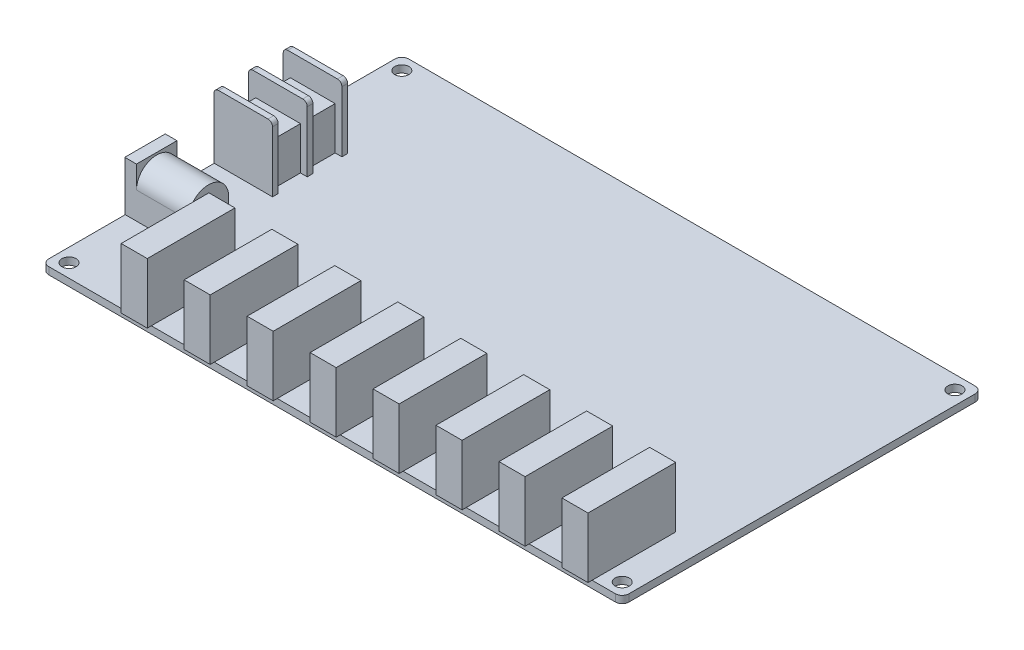
SolidWorks part; units mm, degrees
ref_plane "前视基准面" through (0, 0, 0) normal (0, 0, 1) x (1, 0, 0)
ref_plane "上视基准面" through (0, 0, 0) normal (0, 1, 0) x (1, 0, 0)
ref_plane "右视基准面" through (0, 0, 0) normal (1, 0, 0) x (0, 0, -1)
other "Configuration Table"
sketch "草图1" plane through (0, 0, 0) normal (0, 1, 0) x (1, 0, 0)
  line L0 (39.2697, 0) -> (168.2697, 0)
  line L1 (168.2697, 0) -> (168.2697, 80)
  line L2 (168.2697, 80) -> (39.2697, 80)
  line L3 (39.2697, 80) -> (39.2697, 0)
extrude "凸台-拉伸1" add sketch "草图1" along normal blind 1.6 contours L3 L0 L1 L2
sketch "草图2" plane through (0, 1.6, 0) normal (0, 1, 0) x (1, 0, 0)
  circle A0 centre (42.2697, 77) radius 1.575
  circle A1 centre (42.2697, 3) radius 1.575
  circle A2 centre (165.2697, 3) radius 1.575
  circle A3 centre (165.2697, 77) radius 1.575
extrude "切除-拉伸1" cut sketch "草图2" against normal through all
sketch "草图3" plane through (0, 1.6, 0) normal (0, 1, 0) x (1, 0, 0)
  line L0 (39.2697, 0) -> (57.7697, 0)
  line L1 (39.2697, 0) -> (168.2697, 0) construction
  line L2 (57.7697, 0) -> (57.7697, 18.6)
  line L3 (57.7697, 18.6) -> (63.5697, 18.6)
  line L4 (63.5697, 18.6) -> (63.5697, 0)
  line L34 (57.7697, 0) -> (57.7697, -0.9)
  line L35 (57.7697, -0.9) -> (63.5697, -0.9)
  line L36 (63.5697, -0.9) -> (63.5697, 0)
  line L40 (53.2697, 0) -> (71.7697, 0)
  line L41 (71.7697, 0) -> (71.7697, 18.6)
  line L42 (71.7697, 18.6) -> (77.5697, 18.6)
  line L43 (77.5697, 18.6) -> (77.5697, 0)
  line L44 (71.7697, 0) -> (71.7697, -0.9)
  line L45 (71.7697, -0.9) -> (77.5697, -0.9)
  line L46 (77.5697, -0.9) -> (77.5697, 0)
  line L47 (67.2697, 0) -> (85.7697, 0)
  line L48 (85.7697, 0) -> (85.7697, 18.6)
  line L49 (85.7697, 18.6) -> (91.5697, 18.6)
  line L50 (91.5697, 18.6) -> (91.5697, 0)
  line L51 (85.7697, 0) -> (85.7697, -0.9)
  line L52 (85.7697, -0.9) -> (91.5697, -0.9)
  line L53 (91.5697, -0.9) -> (91.5697, 0)
  line L54 (81.2697, 0) -> (99.7697, 0)
  line L55 (99.7697, 0) -> (99.7697, 18.6)
  line L56 (99.7697, 18.6) -> (105.5697, 18.6)
  line L57 (105.5697, 18.6) -> (105.5697, 0)
  line L58 (99.7697, 0) -> (99.7697, -0.9)
  line L59 (99.7697, -0.9) -> (105.5697, -0.9)
  line L60 (105.5697, -0.9) -> (105.5697, 0)
  line L61 (95.2697, 0) -> (113.7697, 0)
  line L62 (113.7697, 0) -> (113.7697, 18.6)
  line L63 (113.7697, 18.6) -> (119.5697, 18.6)
  line L64 (119.5697, 18.6) -> (119.5697, 0)
  line L65 (113.7697, 0) -> (113.7697, -0.9)
  line L66 (113.7697, -0.9) -> (119.5697, -0.9)
  line L67 (119.5697, -0.9) -> (119.5697, 0)
  line L68 (109.2697, 0) -> (127.7697, 0)
  line L69 (127.7697, 0) -> (127.7697, 18.6)
  line L70 (127.7697, 18.6) -> (133.5697, 18.6)
  line L71 (133.5697, 18.6) -> (133.5697, 0)
  line L72 (127.7697, 0) -> (127.7697, -0.9)
  line L73 (127.7697, -0.9) -> (133.5697, -0.9)
  line L74 (133.5697, -0.9) -> (133.5697, 0)
  line L75 (123.2697, 0) -> (141.7697, 0)
  line L76 (141.7697, 0) -> (141.7697, 18.6)
  line L77 (141.7697, 18.6) -> (147.5697, 18.6)
  line L78 (147.5697, 18.6) -> (147.5697, 0)
  line L79 (141.7697, 0) -> (141.7697, -0.9)
  line L80 (141.7697, -0.9) -> (147.5697, -0.9)
  line L81 (147.5697, -0.9) -> (147.5697, 0)
  line L82 (137.2697, 0) -> (155.7697, 0)
  line L83 (155.7697, 0) -> (155.7697, 18.6)
  line L84 (155.7697, 18.6) -> (161.5697, 18.6)
  line L85 (161.5697, 18.6) -> (161.5697, 0)
  line L86 (155.7697, 0) -> (155.7697, -0.9)
  line L87 (155.7697, -0.9) -> (161.5697, -0.9)
  line L88 (161.5697, -0.9) -> (161.5697, 0)
  line M11 (39.2697, 0) -> (168.2697, 0)
  dimension "D1" = 8
extrude "凸台-拉伸2" add sketch "草图3" along normal blind 13.4 contours L4 L3 L2 M11 | L35 L36 L34 M11 | L43 L42 L41 M11 | L50 L49 L48 M11 | L57 L56 L55 M11 | L64 L63 L62 M11 | L71 L70 L69 M11 | L78 L77 L76 M11 | L85 L84 L83 M11 | L87 L88 L86 M11
fillet "圆角1" radius 1.5 4 edges at (39.2697, 0.8, -80) (168.2697, 0.8, -80) (168.2697, 0.8, 0) (39.2697, 0.8, 0)
sketch "草图4" plane through (0, 1.6, 0) normal (0, 1, 0) x (1, 0, 0)
  line L1 (39.2697, 78.5) -> (39.2697, 1.5) construction
  line L2 (39.2697, 18.5) -> (39.2697, 27.5)
  line L3 (39.2697, 27.5) -> (53.2697, 27.5)
  line L4 (53.2697, 27.5) -> (53.2697, 18.5)
  line L5 (53.2697, 18.5) -> (39.2697, 18.5)
extrude "凸台-拉伸3" add sketch "草图4" along normal blind 11
sketch "草图5" plane through (39.2697, 0, 0) normal (-1, 0, 0) x (0, 0, 1)
  line L0 (-27.5, 1.6) -> (-18.5, 1.6)
  line L1 (-18.5, 1.6) -> (-18.5, 12.6)
  line L2 (-27.5, 12.6) -> (-18.5, 12.6) construction
  line L3 (-18.5, 12.6) -> (-18.5, 1.6) construction
  line L4 (-18.5, 12.6) -> (-27.5, 12.6)
  line L5 (-27.5, 12.6) -> (-27.5, 1.6)
extrude "凸台-拉伸4" add sketch "草图5" along normal blind 0.1
sketch "草图6" plane through (53.2697, 0, 0) normal (1, 0, 0) x (0, 0, -1)
  line L4 (27.5, 12.6) -> (27.5, 1.6) construction
  line L5 (18.5, 12.6) -> (18.5, 1.6) construction
  line L6 (18.5, 12.6) -> (18.5, 7.6)
  line L7 (27.5, 12.6) -> (27.5, 7.6)
  line L8 (18.5, 12.6) -> (27.5, 12.6) construction
  line L9 (18.5, 12.6) -> (27.5, 12.6)
  arc A0 (27.5, 7.6) -> (18.5, 7.6) centre (23, 7.6) ccw
extrude "切除-拉伸2" cut sketch "草图6" against normal blind 11.5
sketch "草图7" plane through (39.1697, 0, 0) normal (-1, 0, 0) x (0, 0, 1)
  circle A3 centre (-23, 7.6) radius 3.2
extrude "切除-拉伸3" cut sketch "草图7" against normal blind 11.5
sketch "草图8" plane through (50.6697, 0, 0) normal (-1, 0, 0) x (0, 0, 1)
  circle A0 centre (-23, 7.6) radius 0.75
extrude "凸台-拉伸5" add sketch "草图8" along normal blind 10
sketch "草图9" plane through (0, 1.6, 0) normal (0, 1, 0) x (1, 0, 0)
  line L3 (39.2697, 38.3) -> (52.2197, 38.3)
  line L5 (52.2197, 55) -> (39.2697, 55)
  line L9 (52.2197, 39.565) -> (52.2197, 38.3)
  line L11 (52.2197, 53.73) -> (50.7197, 53.73)
  line L12 (50.7197, 53.73) -> (50.7197, 47.285)
  line L13 (50.7197, 47.285) -> (52.2197, 47.285)
  line L14 (52.2197, 47.285) -> (52.2197, 46.015)
  line L15 (52.2197, 46.015) -> (50.7197, 46.015)
  line L16 (50.7197, 46.015) -> (50.7197, 39.565)
  line L17 (50.7197, 39.565) -> (52.2197, 39.565)
  line L18 (52.2197, 53.73) -> (52.2197, 55)
  line L19 (40.7697, 39.565) -> (39.2697, 39.565)
  line L20 (40.7697, 46.015) -> (40.7697, 39.565)
  line L21 (39.2697, 46.015) -> (40.7697, 46.015)
  line L23 (40.7697, 47.285) -> (39.2697, 47.285)
  line L24 (40.7697, 53.73) -> (40.7697, 47.285)
  line L25 (39.2697, 53.73) -> (40.7697, 53.73)
  line L27 (39.2697, 55) -> (39.1697, 55)
  line L28 (39.1697, 55) -> (39.1697, 53.73)
  line L29 (39.1697, 53.73) -> (39.2697, 53.73)
  line L30 (39.2697, 47.285) -> (39.1697, 47.285)
  line L31 (39.1697, 47.285) -> (39.1697, 46.015)
  line L32 (39.1697, 46.015) -> (39.2697, 46.015)
  line L33 (39.2697, 39.565) -> (39.2197, 39.565)
  line L34 (39.2197, 39.565) -> (39.2197, 38.3)
  line L35 (39.2197, 38.3) -> (39.2697, 38.3)
extrude "凸台-拉伸6" add sketch "草图9" along normal blind 14.5
sketch "草图10" plane through (39.2197, 0, 0) normal (-1, 0, 0) x (0, 0, 1)
  line L0 (-39.565, 16.1) -> (-39.565, 11.1)
  line L1 (-39.565, 16.1) -> (-39.565, 1.6) construction
  line L2 (-39.565, 11.1) -> (-46.015, 11.1)
  line L3 (-46.015, 16.1) -> (-46.015, 1.6) construction
  line L4 (-46.015, 11.1) -> (-46.015, 16.1)
  line L5 (-46.015, 16.1) -> (-39.565, 16.1)
  line L6 (-47.285, 16.1) -> (-47.285, 11.1)
  line L7 (-47.285, 16.1) -> (-47.285, 1.6) construction
  line L8 (-47.285, 11.1) -> (-53.73, 11.1)
  line L9 (-53.73, 16.1) -> (-53.73, 1.6) construction
  line L10 (-53.73, 11.1) -> (-53.73, 16.1)
  line L11 (-53.73, 16.1) -> (-47.285, 16.1)
extrude "切除-拉伸4" cut sketch "草图10" against normal blind 14.5
fillet "圆角2" radius 1 6 edges at (52.2197, 16.1, -38.9325) (52.2197, 16.1, -46.65) (52.2197, 16.1, -54.365) (39.1697, 16.1, -46.65) (39.2197, 16.1, -38.9325) (39.1697, 16.1, -54.365)
